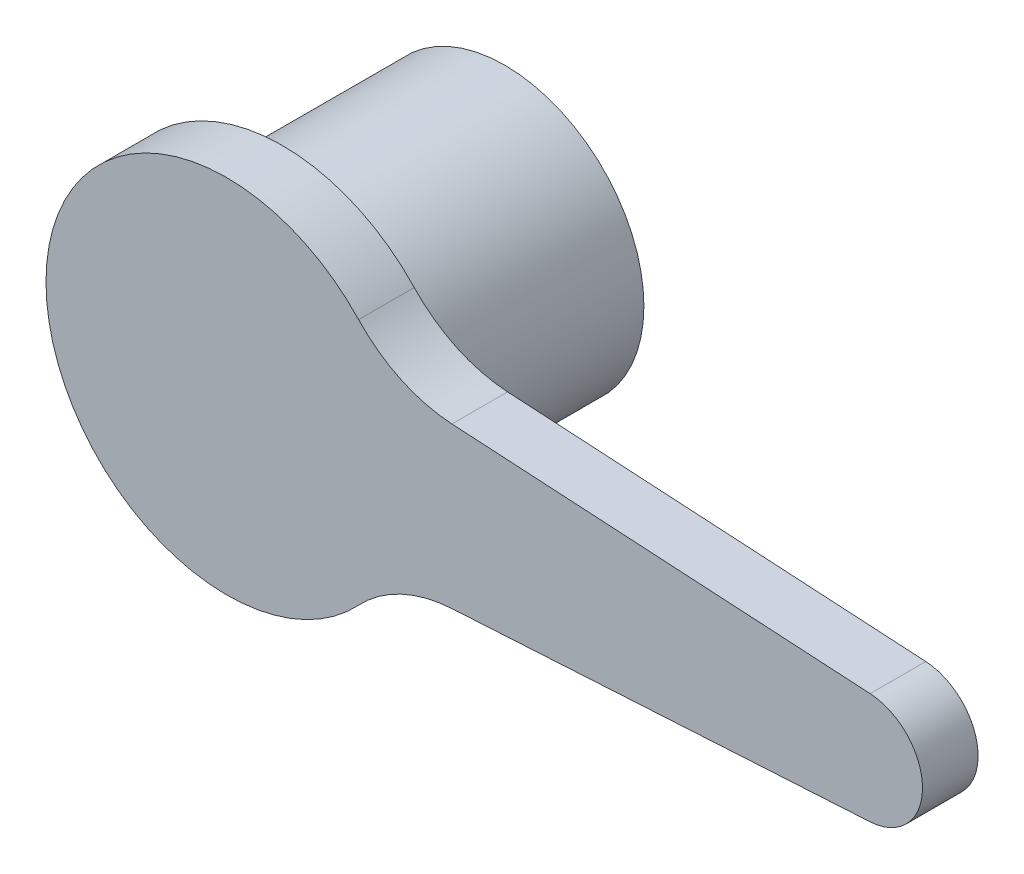
SolidWorks part; units mm, degrees
ref_plane "Front Plane" through (0, 0, 0) normal (0, 0, 1) x (1, 0, 0)
ref_plane "Top Plane" through (0, 0, 0) normal (0, 1, 0) x (1, 0, 0)
ref_plane "Right Plane" through (0, 0, 0) normal (1, 0, 0) x (0, 0, -1)
sketch "Sketch3" plane through (0, 0, 0) normal (0, 0, 1) x (1, 0, 0)
  line L0 (231.3425, 19.9659) -> (80.9673, 28.7522)
  line L1 (0, 0) -> (210.1759, 0) construction
  line L2 (231.3425, -19.9659) -> (80.9673, -28.7522)
  arc A0 (47.4126, 44.464) -> (47.4126, -44.464) centre (0, 0) ccw
  arc A1 (231.3425, -19.9659) -> (231.3425, 19.9659) centre (230.1759, 0) ccw
  arc A2 (80.9673, 28.7522) -> (47.4126, 44.464) centre (83.8838, 78.6671) cw
  arc A3 (80.9673, -28.7522) -> (47.4126, -44.464) centre (83.8838, -78.6671) ccw
  point P1 (0, 0)
  point P8 (0, 0)
  point P9 (0, 0)
  dimension "D1" = 130
  dimension "D2" = 40
  dimension "D3" = 50
extrude "Boss-Extrude1" add sketch "Sketch3" along normal blind 20
sketch "Sketch4" plane through (0, 0, 0) normal (0, 0, -1) x (-1, 0, 0)
  line L0 (-231.3762, -12.4422) -> (-102.4006, -24.8845)
  line L1 (-231.3762, 12.4422) -> (-102.4006, 24.8845)
  arc A0 (-231.3762, 12.4422) -> (-231.3762, -12.4422) centre (-230.1759, 0) ccw
  arc A1 (-102.4006, -24.8845) -> (-102.4006, 24.8845) centre (-100, 0) ccw
  dimension "D1" = 25
  dimension "D2" = 50
  dimension "D3" = 100
extrude "Cut-Extrude1" cut sketch "Sketch4" against normal blind 10
sketch "Sketch9" plane through (0, 0, 0) normal (0, 0, -1) x (-1, 0, 0)
  circle A0 centre (0, 0) radius 50
extrude "Boss-Extrude4" add sketch "Sketch9" along normal blind 80
sketch "Sketch10" plane through (0, 0, -80) normal (0, 0, -1) x (-1, 0, 0)
  line L1 (0, 46.188) -> (-40, 23.094)
  line L2 (-40, 23.094) -> (-40, -23.094)
  line L3 (-40, -23.094) -> (0, -46.188)
  line L4 (0, -46.188) -> (40, -23.094)
  line L5 (40, -23.094) -> (40, 23.094)
  line L6 (40, 23.094) -> (0, 46.188)
  circle A0 centre (0, 0) radius 40 construction
extrude "Cut-Extrude4" cut sketch "Sketch10" against normal blind 75
